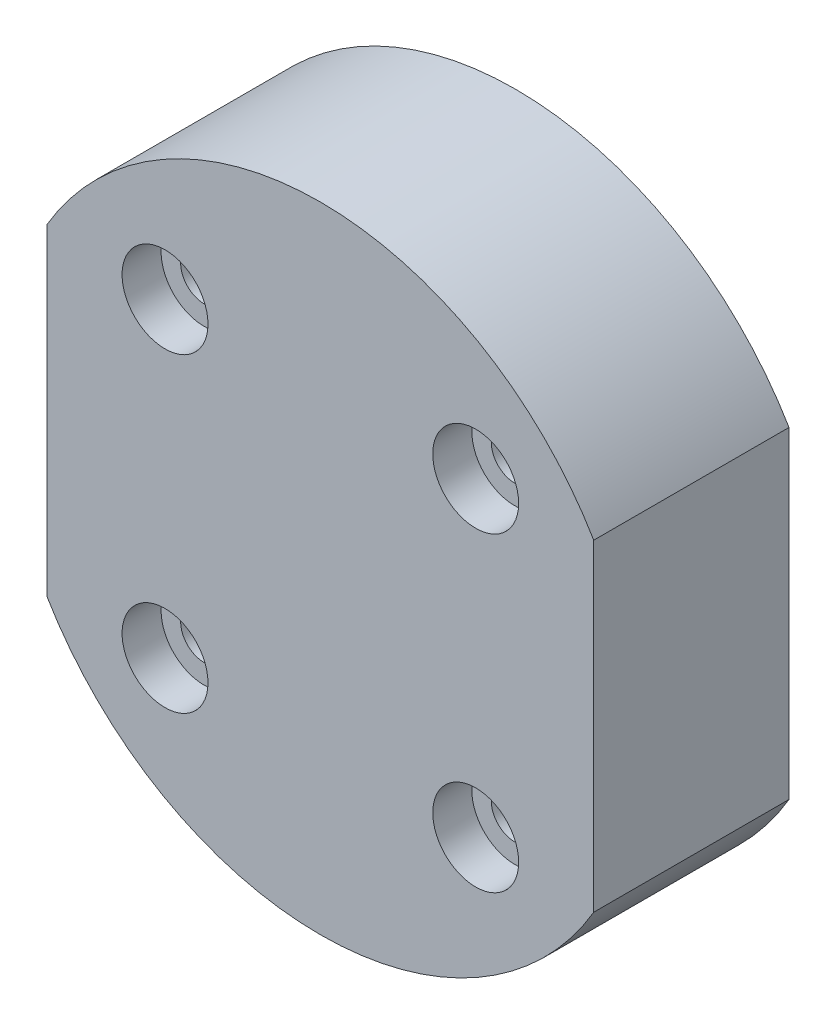
SolidWorks part; units mm, degrees
ref_plane "Front Plane" through (0, 0, 0) normal (0, 0, 1) x (1, 0, 0)
ref_plane "Top Plane" through (0, 0, 0) normal (0, 1, 0) x (1, 0, 0)
ref_plane "Right Plane" through (0, 0, 0) normal (1, 0, 0) x (0, 0, -1)
sketch "Sketch1" plane through (0, 0, 0) normal (0, 0, 1) x (1, 0, 0)
  circle A0 centre (0, 0) radius 16.25
  dimension "D1" = 32.5
extrude "Boss-Extrude1" add sketch "Sketch1" against normal blind 10
sketch "Sketch2" plane through (0, 0, 0) normal (0, 0, 1) x (1, 0, 0)
  line L0 (14, 8.25) -> (14, -8.25)
  line L1 (-14, 8.25) -> (-14, -8.25)
  line L2 (-14, 8.25) -> (-24, 8.25)
  line L3 (-24, 8.25) -> (-24, -8.25)
  line L4 (-24, -8.25) -> (-14, -8.25)
  line L5 (14, 8.25) -> (24, 8.25)
  line L6 (24, 8.25) -> (24, -8.25)
  line L7 (24, -8.25) -> (14, -8.25)
  circle A0 centre (0, 0) radius 16.25 construction
  dimension "D1" = 14
  dimension "D2" = 10
  dimension "D3" = 10
extrude "Cut-Extrude1" cut sketch "Sketch2" against normal through all both and the other way through all
sketch "Sketch4" plane through (0, 0, 0) normal (0, 0, 1) x (1, 0, 0)
  line L0 (0, 0) -> (7.3829, 0) construction
  line L1 (0, 0) -> (7.955, 7.955) construction
  circle A0 centre (0, 0) radius 11.25 construction
  arc A1 (14, 8.25) -> (-14, 8.25) centre (0, 0) ccw construction
  point P6 (7.955, 7.955)
  point P10 (7.955, -7.955)
  point P11 (-7.955, -7.955)
  point P12 (-7.955, 7.955)
  dimension "D1" = 5
  dimension "D3" = 45
  dimension "D2" = 4
hole_wizard "CBORE for M2 SHCS1" positions "Sketch4" profile "Sketch13" counterbore size "M2" standard "ANSI Metric" end condition through all
sketch "Sketch13" plane through (-7.955, 7.955, 0) normal (1, 0, 0) x (0, -1, 0)
  line L0 (0, 0) -> (0, 10)
  line L1 (0, 10) -> (1.2, 10)
  line L3 (1.2, 10) -> (1.2, 2)
  line L4 (1.2, 2) -> (2.2, 2)
  line L5 (2.2, 2) -> (2.2, 0)
  line L7 (2.2, 0) -> (0, 0)
  line L11 (0, -6.35) -> (0, 107.95) construction
  dimension "Thru Hole Dia." = 2.4
  dimension "Thru Hole Depth" = 10
  dimension "C'Bore Dia." = 4.4
  dimension "C'Bore Depth" = 2
